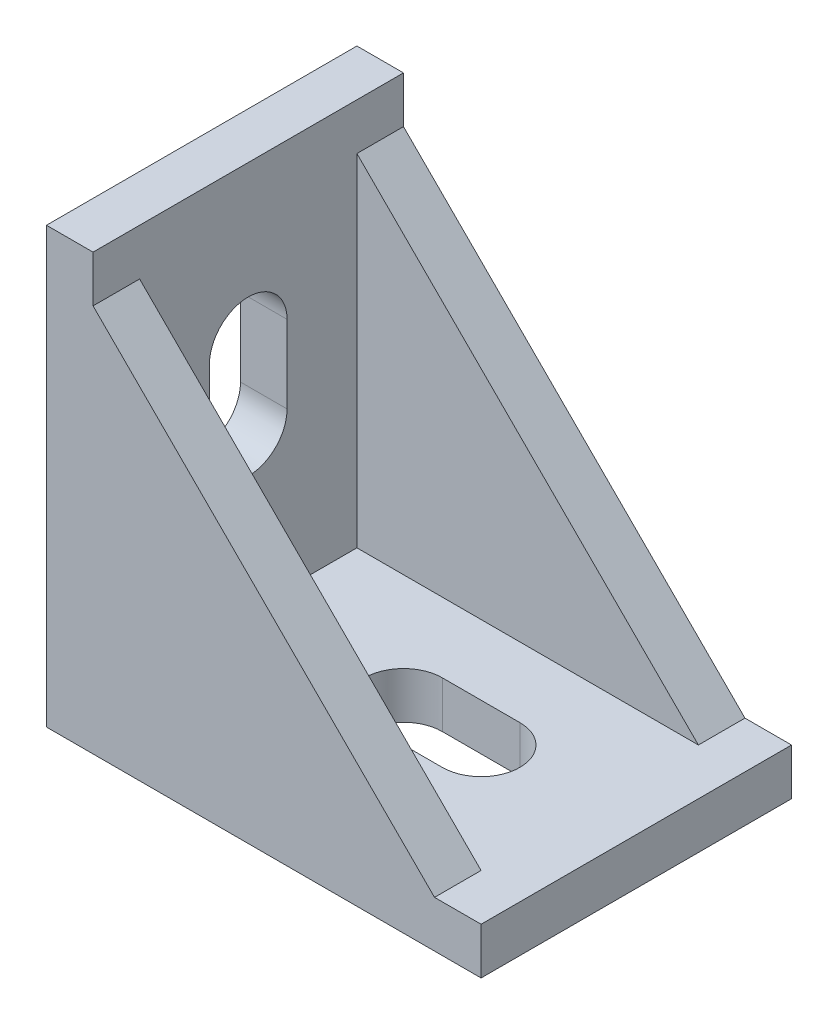
SolidWorks part; units mm, degrees
ref_plane "Front Plane" through (0, 0, 0) normal (0, 0, 1) x (1, 0, 0)
ref_plane "Top Plane" through (0, 0, 0) normal (0, 1, 0) x (1, 0, 0)
ref_plane "Right Plane" through (0, 0, 0) normal (1, 0, 0) x (0, 0, -1)
sketch "Sketch1" plane through (0, 0, 0) normal (0, 0, 1) x (1, 0, 0)
  line L0 (0, 0) -> (0, 28)
  line L1 (0, 28) -> (3, 28)
  line L2 (3, 28) -> (3, 25)
  line L3 (0, 0) -> (28, 0)
  line L4 (28, 0) -> (28, 3)
  line L5 (28, 3) -> (25, 3)
  line L6 (25, 3) -> (3, 25)
extrude "Boss-Extrude1" add sketch "Sketch1" against normal blind 20
ref_plane "Plane1" through (0, 0, -3) normal (0, 0, 1) x (1, 0, 0)
sketch "Sketch2" plane through (0, 0, -3) normal (0, 0, 1) x (1, 0, 0)
  line L0 (3, 25) -> (3, 3)
  line L1 (3, 3) -> (25, 3)
  line L2 (25, 3) -> (3, 25)
extrude "Cut-Extrude1" cut sketch "Sketch2" against normal blind 14
sketch "Sketch3" plane through (0, 3, 0) normal (0, 1, 0) x (1, 0, 0)
  line L0 (18, 10) -> (13, 10) construction
  line L1 (18, 7.5) -> (13, 7.5)
  line L2 (18, 12.5) -> (13, 12.5)
  line L3 (28, 20) -> (28, 0) construction
  arc A0 (18, 7.5) -> (18, 12.5) centre (18, 10) ccw
  arc A1 (13, 12.5) -> (13, 7.5) centre (13, 10) ccw
  point P2 (15.5, 10)
  point P9 (28, 10)
  dimension "D1" = 2.5
  dimension "D2" = 0
  dimension "D3" = 12.5
  dimension "D4" = 5
extrude "Cut-Extrude2" cut sketch "Sketch3" against normal blind 14
sketch "Sketch4" plane through (3, 0, 0) normal (1, 0, 0) x (0, 0, -1)
  line L0 (10, 13) -> (10, 18) construction
  line L1 (7.5, 13) -> (7.5, 18)
  line L2 (12.5, 13) -> (12.5, 18)
  line L3 (20, 28) -> (0, 28) construction
  arc A0 (7.5, 13) -> (12.5, 13) centre (10, 13) ccw
  arc A1 (12.5, 18) -> (7.5, 18) centre (10, 18) ccw
  point P2 (10, 15.5)
  dimension "D3" = 2.5
  dimension "D1" = 12.5
  dimension "D2" = 5
extrude "Cut-Extrude3" cut sketch "Sketch4" against normal blind 14
